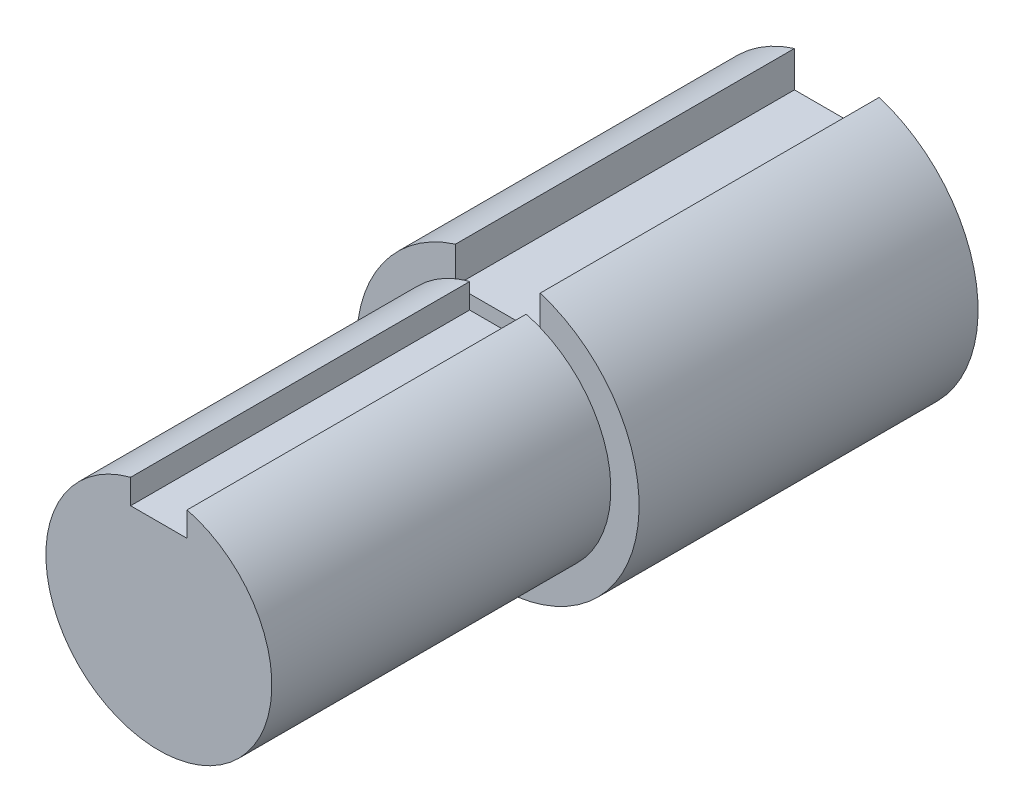
SolidWorks part; units mm, degrees
ref_plane "Front" through (0, 0, 0) normal (0, 0, 1) x (1, 0, 0)
ref_plane "Top" through (0, 0, 0) normal (0, 1, 0) x (1, 0, 0)
ref_plane "Right" through (0, 0, 0) normal (1, 0, 0) x (0, 0, -1)
sketch "Sketch1" plane through (0, 0, 0) normal (0, 0, 1) x (1, 0, 0)
  line L0 (-2.3813, 7.5719) -> (-2.3813, 5.5562)
  line L1 (-2.3813, 5.5562) -> (2.3813, 5.5562)
  line L2 (2.3813, 5.5562) -> (2.3813, 7.5719)
  arc A0 (-2.3813, 7.5719) -> (2.3813, 7.5719) centre (0, 0) ccw
  point P5 (0, 5.5562)
  dimension "D1" = 15.875
  dimension "D2" = 4.7625
  dimension "D3" = 5.5562
extrude "Boss-Extrude1" add sketch "Sketch1" along normal blind 19.05
sketch "Sketch2" plane through (0, 0, 19.05) normal (0, 0, 1) x (1, 0, 0)
  line L0 (-1.5875, 6.1484) -> (-1.5875, 4.7625)
  line L1 (-1.5875, 4.7625) -> (1.5875, 4.7625)
  line L2 (1.5875, 4.7625) -> (1.5875, 6.1484)
  arc A0 (-1.5875, 6.1484) -> (1.5875, 6.1484) centre (0, 0) ccw
  point P5 (0, 4.7625)
  dimension "D1" = 12.7
  dimension "D2" = 4.7625
  dimension "D3" = 3.175
extrude "Boss-Extrude2" add sketch "Sketch2" along normal blind 19.05
